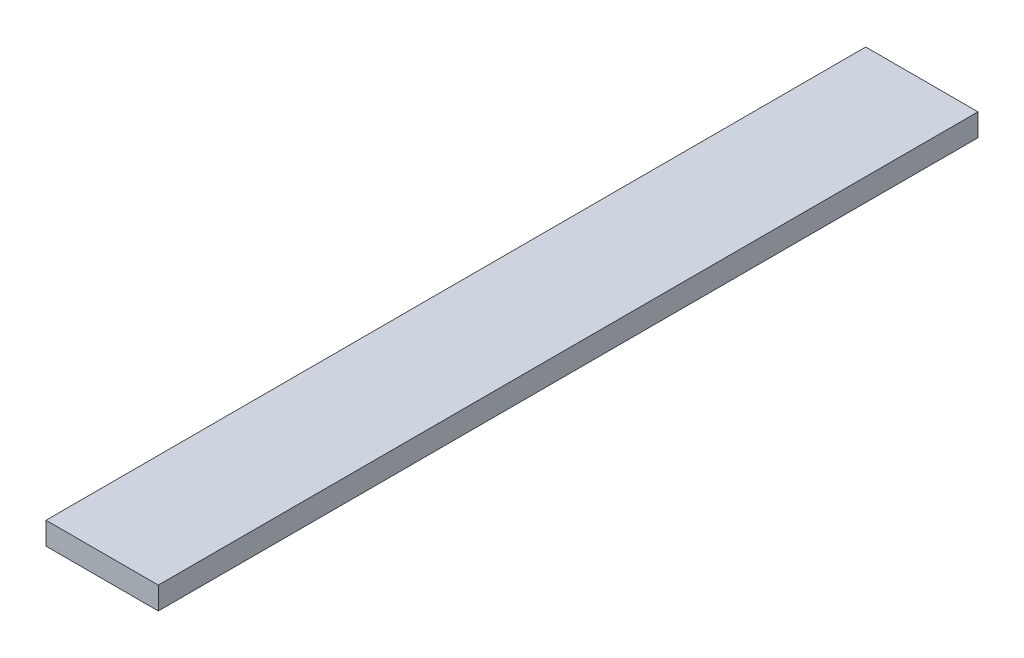
SolidWorks part; units mm, degrees
material "BUTYL"
ref_plane "Front Plane" through (0, 0, 0) normal (0, 0, 1) x (1, 0, 0)
ref_plane "Top Plane" through (0, 0, 0) normal (0, 1, 0) x (1, 0, 0)
ref_plane "Right Plane" through (0, 0, 0) normal (1, 0, 0) x (0, 0, -1)
sketch "Sketch1" plane through (0, 0, 0) normal (0, 1, 0) x (1, 0, 0)
  line L1 (-2.5, 18.25) -> (2.5, 18.25)
  line L2 (-2.5, 18.25) -> (-2.5, -18.25)
  line L3 (-2.5, -18.25) -> (2.5, -18.25)
  line L4 (2.5, 18.25) -> (2.5, -18.25)
  line L5 (-2.5, 18.25) -> (2.5, -18.25) construction
  line L6 (-2.5, -18.25) -> (2.5, 18.25) construction
  point P0 (0, 0)
  dimension "D1" = 36.5
  dimension "D2" = 5
extrude "Boss-Extrude1" add sketch "Sketch1" along normal blind 1
